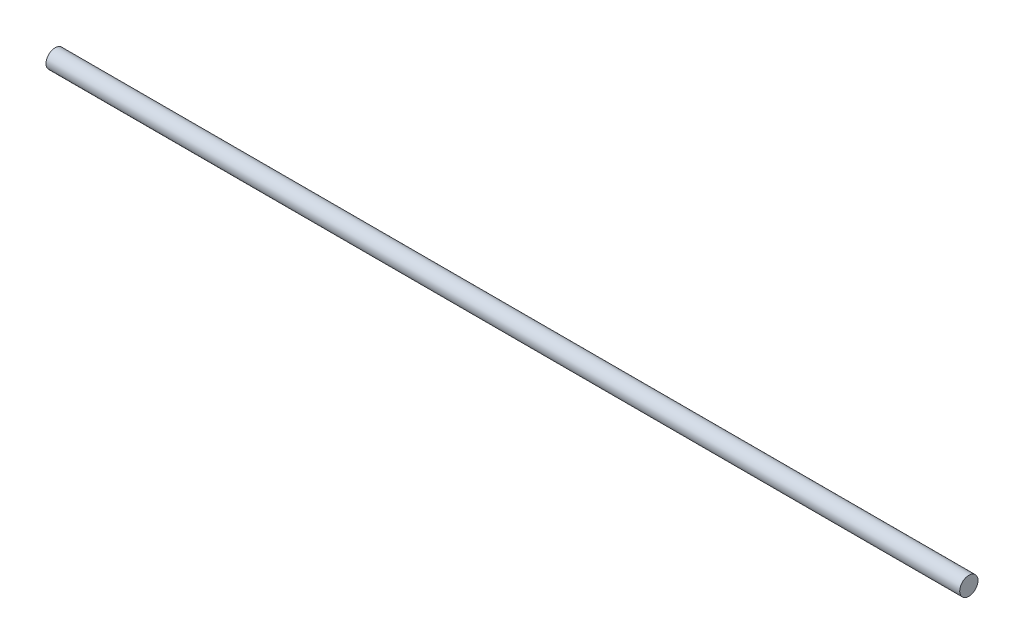
SolidWorks part; units mm, degrees
ref_plane "Top" through (0, 0, 0) normal (0, 0, 1) x (1, 0, 0)
ref_plane "Front" through (0, 0, 0) normal (0, 1, 0) x (1, 0, 0)
ref_plane "Right" through (0, 0, 0) normal (1, 0, 0) x (0, 0, -1)
sketch "Section Sketch" plane through (0, 0, 0) normal (1, 0, 0) x (0, 0, -1)
  circle A0 centre (0, 0) radius 4
  dimension "Diameter" = 8
extrude "Extrude Length" add sketch "Section Sketch" along normal blind 400
